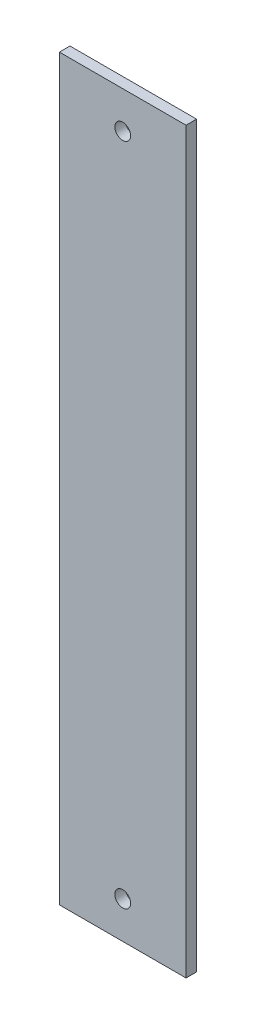
SolidWorks part; units mm, degrees
ref_plane "Front Plane" through (0, 0, 0) normal (0, 0, 1) x (1, 0, 0)
ref_plane "Top Plane" through (0, 0, 0) normal (0, 1, 0) x (1, 0, 0)
ref_plane "Right Plane" through (0, 0, 0) normal (1, 0, 0) x (0, 0, -1)
sketch "Sketch2" plane through (0, 0, 0) normal (0, 0, 1) x (1, 0, 0)
  line L0 (12, 140) -> (12, 0) construction
  line L1 (0, 0) -> (24, 0)
  line L2 (0, 0) -> (0, 140)
  line L3 (0, 140) -> (24, 140)
  line L4 (24, 0) -> (24, 140)
  circle A0 centre (12, 133) radius 1.5
  circle A1 centre (12, 7) radius 1.5
  dimension "D3" = 3
  dimension "D5" = 3
  dimension "D1" = 140
  dimension "D2" = 24
  dimension "D4" = 7
  dimension "D6" = 7
extrude "Boss-Extrude1" add sketch "Sketch2" along normal blind 2
